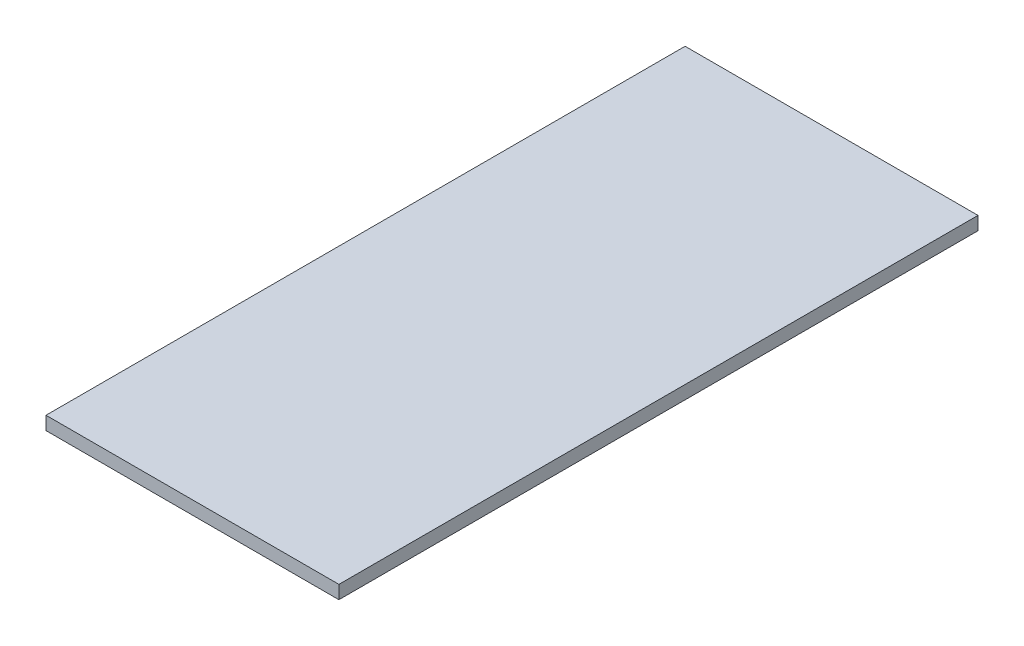
SolidWorks part; units mm, degrees
ref_plane "Front Plane" through (0, 0, 0) normal (0, 0, 1) x (1, 0, 0)
ref_plane "Top Plane" through (0, 0, 0) normal (0, 1, 0) x (1, 0, 0)
ref_plane "Right Plane" through (0, 0, 0) normal (1, 0, 0) x (0, 0, -1)
sketch "Sketch1" plane through (0, 0, 0) normal (0, 1, 0) x (1, 0, 0)
  line L1 (0, 0) -> (-69.85, 0)
  line L2 (0, 0) -> (0, 152.4)
  line L3 (0, 152.4) -> (-69.85, 152.4)
  line L4 (-69.85, 0) -> (-69.85, 152.4)
  dimension "D1" = 152.4
  dimension "D2" = 69.85
extrude "Boss-Extrude1" add sketch "Sketch1" along normal blind 3.175
